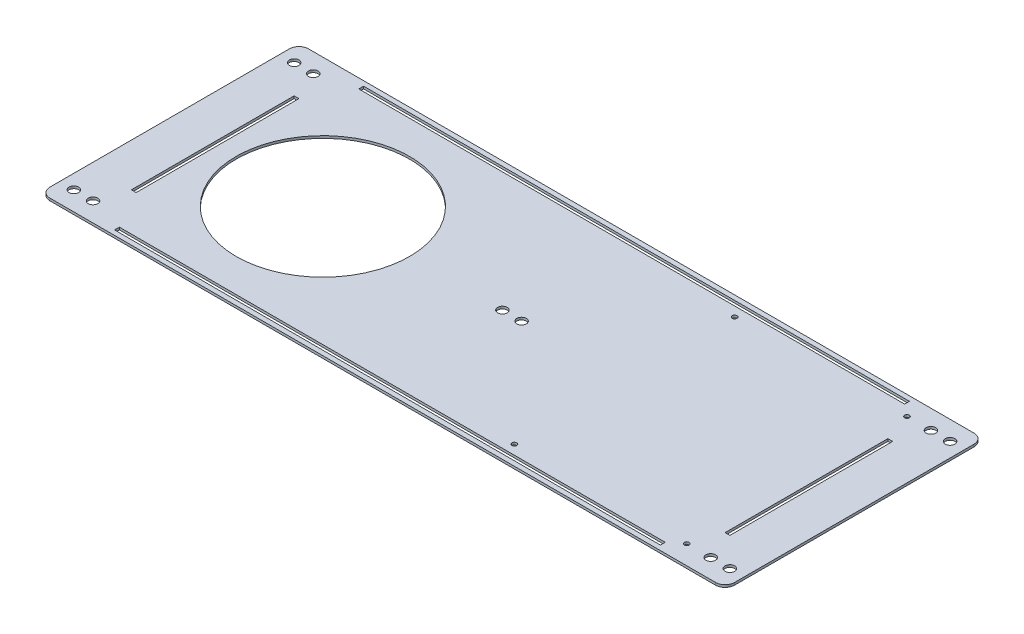
SolidWorks part; units mm, degrees
ref_plane "Front Plane" through (0, 0, 0) normal (0, 0, 1) x (1, 0, 0)
ref_plane "Top Plane" through (0, 0, 0) normal (0, 1, 0) x (1, 0, 0)
ref_plane "Right Plane" through (0, 0, 0) normal (1, 0, 0) x (0, 0, -1)
sketch "Sketch1" plane through (0, 0, 0) normal (0, 1, 0) x (1, 0, 0)
  line L1 (0, 0) -> (454.025, 0)
  line L2 (0, 0) -> (0, 171.45)
  line L3 (0, 171.45) -> (454.025, 171.45)
  line L4 (454.025, 0) -> (454.025, 171.45)
  dimension "D1" = 171.45
  dimension "D2" = 454.025
extrude "Boss-Extrude1" add sketch "Sketch1" along normal blind 1.5875
fillet "Fillet1" radius 6.35 4 edges at (454.025, 0.7937, 0) (0, 0.7937, 0) (454.025, 0.7937, -171.45) (0, 0.7937, -171.45)
sketch "Sketch3" plane through (0, 1.5875, 0) normal (0, 1, 0) x (1, 0, 0)
  line L0 (0, 165.1) -> (0, 6.35) construction
  line L1 (46.0375, 168.275) -> (407.9875, 168.275)
  line L2 (46.0375, 168.275) -> (46.0375, 165.1)
  line L3 (46.0375, 165.1) -> (407.9875, 165.1)
  line L4 (407.9875, 168.275) -> (407.9875, 165.1)
  line L5 (28.575, 139.7) -> (31.75, 139.7)
  line L6 (28.575, 139.7) -> (28.575, 31.75)
  line L7 (28.575, 31.75) -> (31.75, 31.75)
  line L8 (31.75, 139.7) -> (31.75, 31.75)
  line L9 (46.0375, 6.35) -> (407.9875, 6.35)
  line L10 (46.0375, 6.35) -> (46.0375, 3.175)
  line L11 (46.0375, 3.175) -> (407.9875, 3.175)
  line L12 (407.9875, 6.35) -> (407.9875, 3.175)
  line L13 (422.275, 31.75) -> (425.45, 31.75)
  line L14 (422.275, 31.75) -> (422.275, 139.7)
  line L15 (422.275, 139.7) -> (425.45, 139.7)
  line L16 (425.45, 31.75) -> (425.45, 139.7)
  line L17 (447.675, 171.45) -> (6.35, 171.45) construction
  line L18 (6.35, 0) -> (447.675, 0) construction
  line L19 (454.025, 6.35) -> (454.025, 165.1) construction
  line L20 (447.675, 171.45) -> (6.35, 171.45) construction
  point P20 (227.0125, 171.45)
  point P21 (227.0125, 168.275)
  point P22 (0, 85.725)
  point P23 (28.575, 85.725)
  dimension "D3" = 3.175
  dimension "D5" = 3.175
  dimension "D6" = 28.575
  dimension "D7" = 28.575
  dimension "D4" = 3.175
  dimension "D1" = 361.95
  dimension "D2" = 107.95
extrude "Cut-Extrude1" cut sketch "Sketch3" against normal through all
sketch "Sketch4" plane through (0, 1.5875, 0) normal (0, 1, 0) x (1, 0, 0)
  line L1 (28.575, 165.1) -> (3.175, 165.1) construction
  line L2 (28.575, 165.1) -> (28.575, 152.4) construction
  line L3 (28.575, 152.4) -> (3.175, 152.4) construction
  line L4 (3.175, 165.1) -> (3.175, 152.4) construction
  line L5 (46.0375, 165.1) -> (407.9875, 165.1) construction
  line L6 (28.575, 139.7) -> (28.575, 31.75) construction
  line L7 (450.85, 165.1) -> (425.45, 165.1) construction
  line L8 (450.85, 165.1) -> (450.85, 152.4) construction
  line L9 (450.85, 152.4) -> (425.45, 152.4) construction
  line L10 (425.45, 165.1) -> (425.45, 152.4) construction
  line L11 (450.85, 19.05) -> (425.45, 19.05) construction
  line L12 (450.85, 19.05) -> (450.85, 6.35) construction
  line L13 (450.85, 6.35) -> (425.45, 6.35) construction
  line L14 (425.45, 19.05) -> (425.45, 6.35) construction
  line L15 (28.575, 19.05) -> (3.175, 19.05) construction
  line L16 (28.575, 19.05) -> (28.575, 6.35) construction
  line L17 (28.575, 6.35) -> (3.175, 6.35) construction
  line L18 (3.175, 19.05) -> (3.175, 6.35) construction
  line L20 (425.45, 31.75) -> (425.45, 139.7) construction
  line L21 (407.9875, 6.35) -> (46.0375, 6.35) construction
  line L22 (239.7125, 92.075) -> (214.3125, 92.075) construction
  line L23 (239.7125, 92.075) -> (239.7125, 79.375) construction
  line L24 (239.7125, 79.375) -> (214.3125, 79.375) construction
  line L25 (214.3125, 92.075) -> (214.3125, 79.375) construction
  line L26 (447.675, 171.45) -> (6.35, 171.45) construction
  line L27 (454.025, 6.35) -> (454.025, 165.1) construction
  circle A0 centre (9.525, 158.75) radius 3.175
  circle A1 centre (22.225, 158.75) radius 3.175
  circle A2 centre (431.8, 158.75) radius 3.175
  circle A3 centre (444.5, 158.75) radius 3.175
  circle A4 centre (431.8, 12.7) radius 3.175
  circle A5 centre (444.5, 12.7) radius 3.175
  circle A6 centre (9.525, 12.7) radius 3.175
  circle A7 centre (22.225, 12.7) radius 3.175
  circle A8 centre (220.6625, 85.725) radius 3.175
  circle A9 centre (233.3625, 85.725) radius 3.175
  point P15 (28.575, 158.75)
  point P24 (450.85, 158.75)
  point P33 (450.85, 12.7)
  point P42 (28.575, 12.7)
  point P54 (239.7125, 85.725)
  point P58 (227.0125, 171.45)
  point P59 (227.0125, 92.075)
  point P62 (454.025, 85.725)
  dimension "D2" = 6.35
  dimension "D6" = 6.35
  dimension "D10" = 6.35
  dimension "D14" = 6.35
  dimension "D22" = 6.35
  dimension "D1" = 12.7
  dimension "D3" = 6.35
  dimension "D4" = 12.7
  dimension "D5" = 12.7
  dimension "D7" = 6.35
  dimension "D8" = 12.7
  dimension "D9" = 12.7
  dimension "D11" = 6.35
  dimension "D12" = 12.7
  dimension "D13" = 12.7
  dimension "D15" = 6.35
  dimension "D16" = 12.7
  dimension "D17" = 25.4
  dimension "D18" = 25.4
  dimension "D19" = 25.4
  dimension "D20" = 25.4
  dimension "D21" = 12.7
  dimension "D23" = 6.35
  dimension "D24" = 12.7
  dimension "D25" = 25.4
extrude "Cut-Extrude2" cut sketch "Sketch4" against normal through all
sketch "Sketch6" plane through (0, 1.5875, 0) normal (0, 1, 0) x (1, 0, 0)
  line L0 (454.025, 6.35) -> (454.025, 165.1) construction
  line L1 (296.8625, 163.5125) -> (420.6875, 163.5125) construction
  line L2 (296.8625, 163.5125) -> (296.8625, 7.9375) construction
  line L3 (296.8625, 7.9375) -> (420.6875, 7.9375) construction
  line L4 (420.6875, 163.5125) -> (420.6875, 7.9375) construction
  line L6 (422.275, 139.7) -> (422.275, 31.75) construction
  circle A0 centre (301.625, 158.75) radius 1.5875
  circle A1 centre (415.925, 158.75) radius 1.5875
  circle A2 centre (415.925, 12.7) radius 1.5875
  circle A3 centre (301.625, 12.7) radius 1.5875
  point P12 (454.025, 85.725)
  point P13 (420.6875, 85.725)
  dimension "D1" = 3.175
  dimension "D2" = 114.3
  dimension "D3" = 146.05
  dimension "D4" = 4.7625
  dimension "D5" = 4.7625
  dimension "D6" = 4.7625
  dimension "D7" = 4.7625
  dimension "D8" = 1.5875
extrude "Cut-Extrude3" cut sketch "Sketch6" against normal through all
sketch "Sketch7" plane through (0, 1.5875, 0) normal (0, 1, 0) x (1, 0, 0)
  line L0 (31.75, 31.75) -> (31.75, 139.7) construction
  line L1 (0, 165.1) -> (0, 6.35) construction
  circle A0 centre (101.6, 85.725) radius 57.5
  point P6 (0, 85.725)
  dimension "D2" = 115
  dimension "D1" = 69.85
extrude "Cut-Extrude4" cut sketch "Sketch7" against normal through all
equation "\"D6@Sketch6\"=\"D5@Sketch6\""
equation "\"D7@Sketch6\"=\"D4@Sketch6\""
equation "\"D1@Sketch7\"=5.5/2"
equation "\"D7@Sketch3\"=\"D6@Sketch3\""
